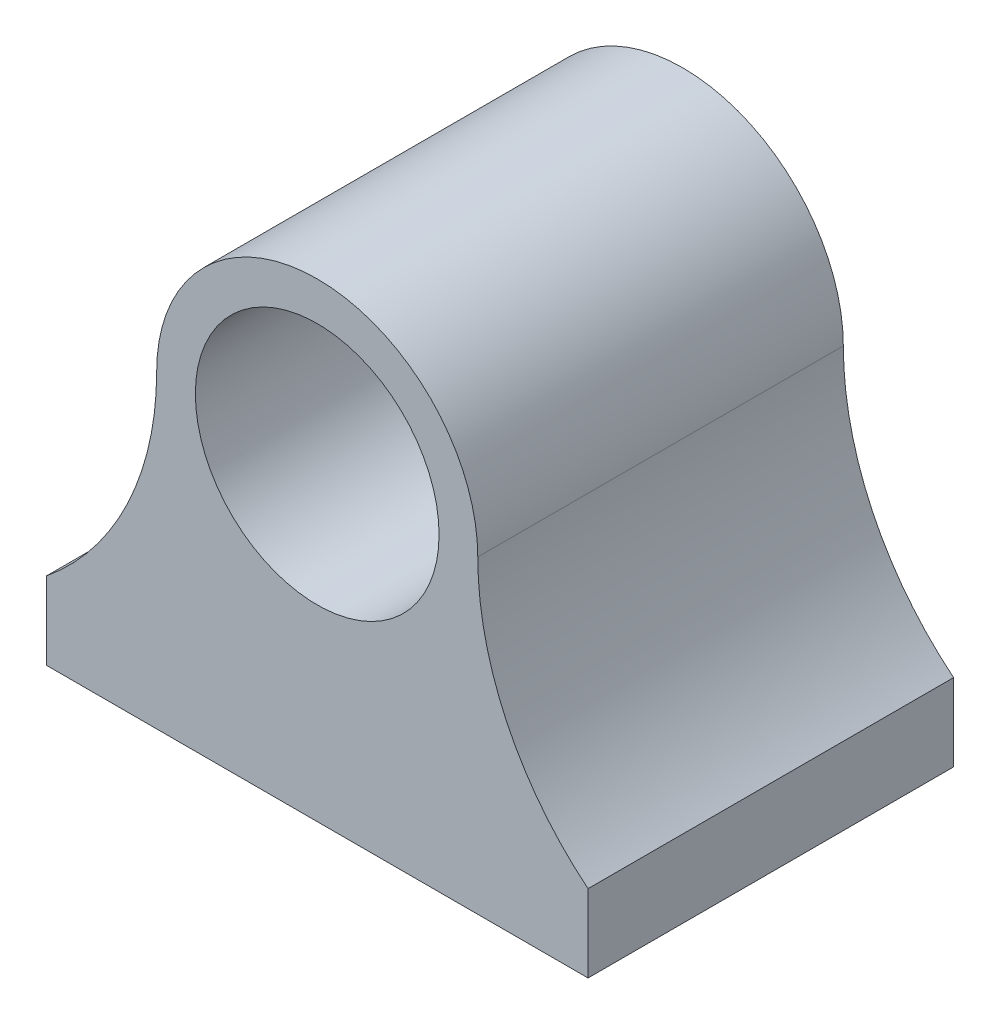
SolidWorks part; units mm, degrees
ref_plane "Front Plane" through (0, 0, 0) normal (0, 0, 1) x (1, 0, 0)
ref_plane "Top Plane" through (0, 0, 0) normal (0, 1, 0) x (1, 0, 0)
ref_plane "Right Plane" through (0, 0, 0) normal (1, 0, 0) x (0, 0, -1)
sketch "Sketch1" plane through (0, 0, 0) normal (0, 0, 1) x (1, 0, 0)
  line L0 (-22.225, -25.4) -> (22.225, -25.4)
  line L2 (22.225, -19.05) -> (22.225, -25.4)
  line L3 (-22.225, -25.4) -> (-22.225, -19.05)
  line L4 (-13.175, 0) -> (0, 0) construction
  line L5 (0, 0) -> (13.175, 0) construction
  circle A1 centre (0, 0) radius 10
  arc A2 (-13.175, 0) -> (-22.225, -19.05) centre (-37.7499, 0) cw
  arc A3 (13.175, 0) -> (-13.175, 0) centre (0, 0) ccw
  arc A4 (13.175, 0) -> (22.225, -19.05) centre (37.7499, 0) ccw
  dimension "D1" = 20
  dimension "D7" = 3.175
  dimension "D2" = 25.4
  dimension "D3" = 22.225
  dimension "D4" = 22.225
  dimension "D5" = 6.35
  dimension "D6" = 6.35
extrude "Boss-Extrude1" add sketch "Sketch1" along normal blind 30 contours A4 A3 A2 L3 L0 L2 A1
